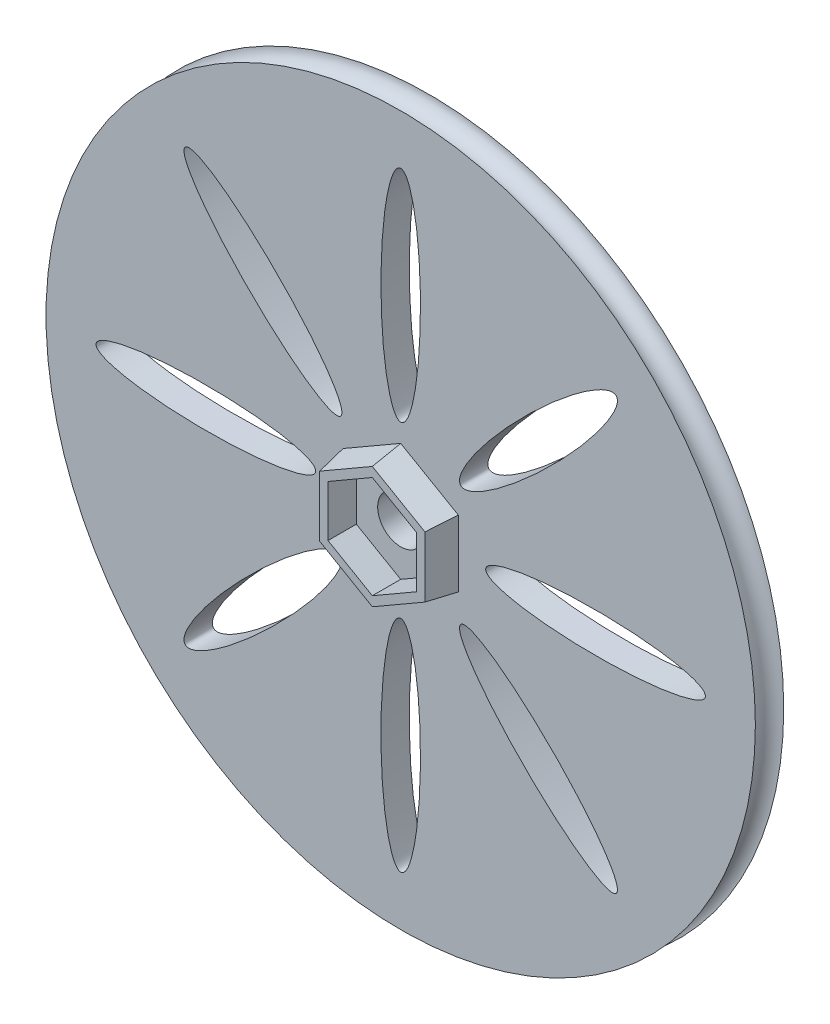
SolidWorks part; units mm, degrees
ref_plane "Front Plane" through (0, 0, 0) normal (0, 0, 1) x (1, 0, 0)
ref_plane "Top Plane" through (0, 0, 0) normal (0, 1, 0) x (1, 0, 0)
ref_plane "Right Plane" through (0, 0, 0) normal (1, 0, 0) x (0, 0, -1)
sketch "Sketch1" plane through (0, 0, 0) normal (0, 0, 1) x (1, 0, 0)
  circle A0 centre (0, 0) radius 50.8
  dimension "D1" = 101.6
extrude "Boss-Extrude1" add sketch "Sketch1" along normal mid plane 4.064
ref_axis "Axis1" through (0, 0, 17.7732) along (0, 0, -1)
sketch "Sketch2" plane through (0, 0, 0) normal (1, 0, 0) x (0, 0, -1)
  line L2 (-2.032, 50.8) -> (-2.032, -50.8) construction
  line L3 (-2.032, 50.8) -> (2.032, 50.8)
  circle A0 centre (0, 50.8) radius 2.032 construction
  arc A1 (-2.032, 50.8) -> (2.032, 50.8) centre (0, 50.8) ccw
revolve "Cut-Revolve1" cut sketch "Sketch2" angle 360 about axis through (0, 0, 17.7732) along (0, 0, -1)
sketch "Sketch3" plane through (0, 0, 0) normal (0, 0, 1) x (1, 0, 0)
  line L0 (0, 0) -> (0, 44.45) construction
  line L1 (0, 0) -> (44.45, 0) construction
  line L2 (-2.8815, 10.16) -> (2.8815, 10.16) construction
  line L3 (2.8814, 10.16) -> (-2.8815, 10.16) construction
  circle A0 centre (0, 0) radius 10.16 construction
  arc A1 (-7.62, 43.792) -> (7.62, 43.792) centre (0, 0) cw
  circle A2 centre (0, 0) radius 44.45 construction
  spline S0 degree 2 poles (0, 10.16) (6.0921, 10.16) (7.62, 43.792) knots 0 0 0 1 1 1
  spline S1 degree 2 poles (0, 10.16) (-6.0921, 10.16) (-7.62, 43.792) knots 0 0 0 1 1 1
  dimension "D1" = 20.32
  dimension "D2" = 88.9
  dimension "D3" = 15.24
sketch "Sketch5" plane through (0, 0, 2.032) normal (0, 0, 1) x (1, 0, 0)
  line L1 (-8.255, -4.766) -> (0, -9.5321)
  line L2 (0, -9.5321) -> (8.255, -4.766)
  line L3 (8.255, -4.766) -> (8.255, 4.766)
  line L4 (8.255, 4.766) -> (0, 9.5321)
  line L5 (0, 9.5321) -> (-8.255, 4.766)
  line L6 (-8.255, 4.766) -> (-8.255, -4.766)
  line L7 (0, 0) -> (0, 44.45) construction
  circle A0 centre (0, 0) radius 8.255 construction
  dimension "D1" = 16.51
extrude "Boss-Extrude2" add sketch "Sketch5" along normal blind 4.064 draft 10
sketch "Sketch6" plane through (0, 0, 6.096) normal (0, 0, 1) x (1, 0, 0)
  line L0 (0, 0) -> (0, 44.45) construction
  line L1 (0, -7.3323) -> (6.35, -3.6662)
  line L2 (6.35, -3.6662) -> (6.35, 3.6662)
  line L3 (6.35, 3.6662) -> (0, 7.3323)
  line L4 (0, 7.3323) -> (-6.35, 3.6662)
  line L5 (-6.35, 3.6662) -> (-6.35, -3.6662)
  line L6 (-6.35, -3.6662) -> (0, -7.3323)
  circle A0 centre (0, 0) radius 6.35 construction
  dimension "D1" = 12.7
extrude "Cut-Extrude3" cut sketch "Sketch6" against normal up to surface (4.064 mm away) up to face at (50.8, 0, 2.032)
sketch "Sketch7" plane through (0, 0, 2.032) normal (0, 0, 1) x (1, 0, 0)
  circle A0 centre (0, 0) radius 3.302
  dimension "D1" = 6.604
extrude "Cut-Extrude4" cut sketch "Sketch7" against normal up to next
sketch "Sketch9" plane through (0, 0, 2.032) normal (0, 0, 1) x (1, 0, 0)
  ellipse E0 centre (0, 27.9065) end of major axis (0, 12.1702) minor radius 2.8362
  ellipse E1 centre (19.7329, 19.7329) end of major axis (8.6056, 8.6056) minor radius 2.8362
  ellipse E2 centre (27.9065, 0) end of major axis (12.1702, 0) minor radius 2.8362
  ellipse E3 centre (19.7329, -19.7329) end of major axis (30.8601, -30.8601) minor radius 2.8362
  ellipse E4 centre (0, -27.9065) end of major axis (0, -12.1702) minor radius 2.8362
  ellipse E5 centre (-19.7329, -19.7329) end of major axis (-8.6056, -8.6056) minor radius 2.8362
  ellipse E6 centre (-27.9065, 0) end of major axis (-12.1702, 0) minor radius 2.8362
  ellipse E7 centre (-19.7329, 19.7329) end of major axis (-30.8601, 30.8601) minor radius 2.8362
  point P51 (0, 0)
extrude "Cut-Extrude6" cut sketch "Sketch9" against normal through all
